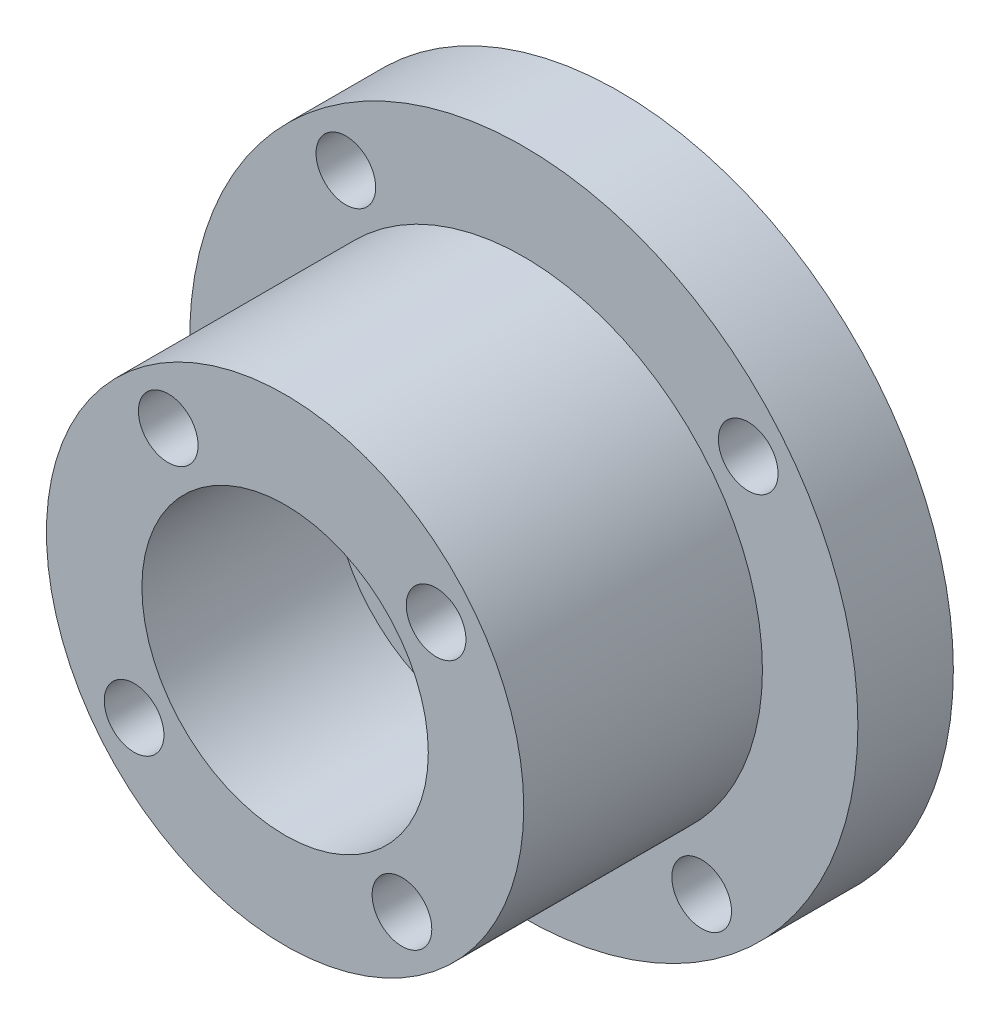
SolidWorks part; units mm, degrees
ref_plane "前视" through (0, 0, 0) normal (0, 0, 1) x (1, 0, 0)
ref_plane "上视" through (0, 0, 0) normal (0, 1, 0) x (1, 0, 0)
ref_plane "右视" through (0, 0, 0) normal (1, 0, 0) x (0, 0, -1)
sketch "草图1" plane through (0, 0, 0) normal (0, 0, 1) x (1, 0, 0)
  circle A0 centre (0, 0) radius 14
  dimension "D1" = 28
extrude "凸台-拉伸1" add sketch "草图1" along normal blind 4
sketch "草图2" plane through (0, 0, 4) normal (0, 0, 1) x (1, 0, 0)
  circle A0 centre (0, 0) radius 10
  dimension "D1" = 20
extrude "凸台-拉伸2" add sketch "草图2" along normal blind 10
sketch "草图3" plane through (0, 0, 14) normal (0, 0, 1) x (1, 0, 0)
  circle A0 centre (0, 0) radius 2.5
  dimension "D1" = 5
extrude "切除-拉伸1" cut sketch "草图3" against normal through all
sketch "草图4" plane through (0, 0, 14) normal (0, 0, 1) x (1, 0, 0)
  circle A0 centre (0, 0) radius 6
  dimension "D1" = 12
extrude "切除-拉伸2" cut sketch "草图4" against normal blind 8
sketch "草图5" plane through (0, 0, 4) normal (0, 0, 1) x (1, 0, 0)
  circle A0 centre (-9.4042, -7.454) radius 1.25
  circle A1 centre (-7.454, 9.4042) radius 1.25
  circle A2 centre (9.4042, 7.454) radius 1.25
  circle A3 centre (7.454, -9.4042) radius 1.25
  point P12 (0, 0)
  dimension "D2" = 2.5
  dimension "D1" = 12
  dimension "D3" = 4
extrude "切除-拉伸3" cut sketch "草图5" against normal blind 8
sketch "草图6" plane through (0, 0, 14) normal (0, 0, 1) x (1, 0, 0)
  circle A0 centre (-6.3267, -4.8962) radius 1.25
  circle A1 centre (-4.8962, 6.3267) radius 1.25
  circle A2 centre (6.3267, 4.8962) radius 1.25
  circle A3 centre (4.8962, -6.3267) radius 1.25
  point P12 (0, 0)
  dimension "D2" = 2.5
  dimension "D1" = 8
  dimension "D3" = 4
extrude "切除-拉伸4" cut sketch "草图6" against normal blind 5
